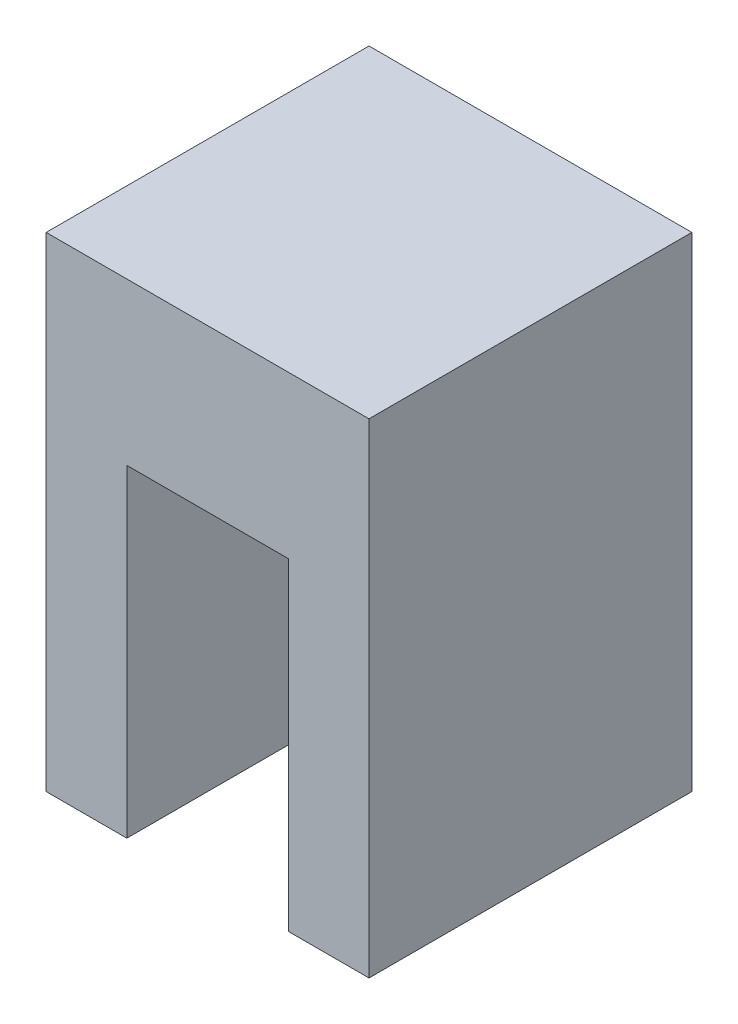
SolidWorks part; units mm, degrees
ref_plane "前视基准面" through (0, 0, 0) normal (0, 0, 1) x (1, 0, 0)
ref_plane "上视基准面" through (0, 0, 0) normal (0, 1, 0) x (1, 0, 0)
ref_plane "右视基准面" through (0, 0, 0) normal (1, 0, 0) x (0, 0, -1)
other "Configuration Table"
sketch "草图1" plane through (0, 0, 0) normal (0, 0, 1) x (1, 0, 0)
  line L0 (0, 14.1326) -> (20, 14.1326)
  line L1 (20, 14.1326) -> (20, -15.8674)
  line L2 (20, -15.8674) -> (15, -15.8674)
  line L3 (0, -15.8674) -> (0, 14.1326)
  line L4 (5, 4.1326) -> (5, -15.8674)
  line L5 (15, 4.1326) -> (15, -15.8674)
  line L6 (5, 4.1326) -> (15, 4.1326)
  line L7 (5, -15.8674) -> (0, -15.8674)
  point P8 (0, 14.1326)
  dimension "D1" = 5
  dimension "D2" = 5
  dimension "D3" = 20
  dimension "D4" = 30
  dimension "D5" = 20
extrude "凸台-拉伸1" add sketch "草图1" along normal blind 20
